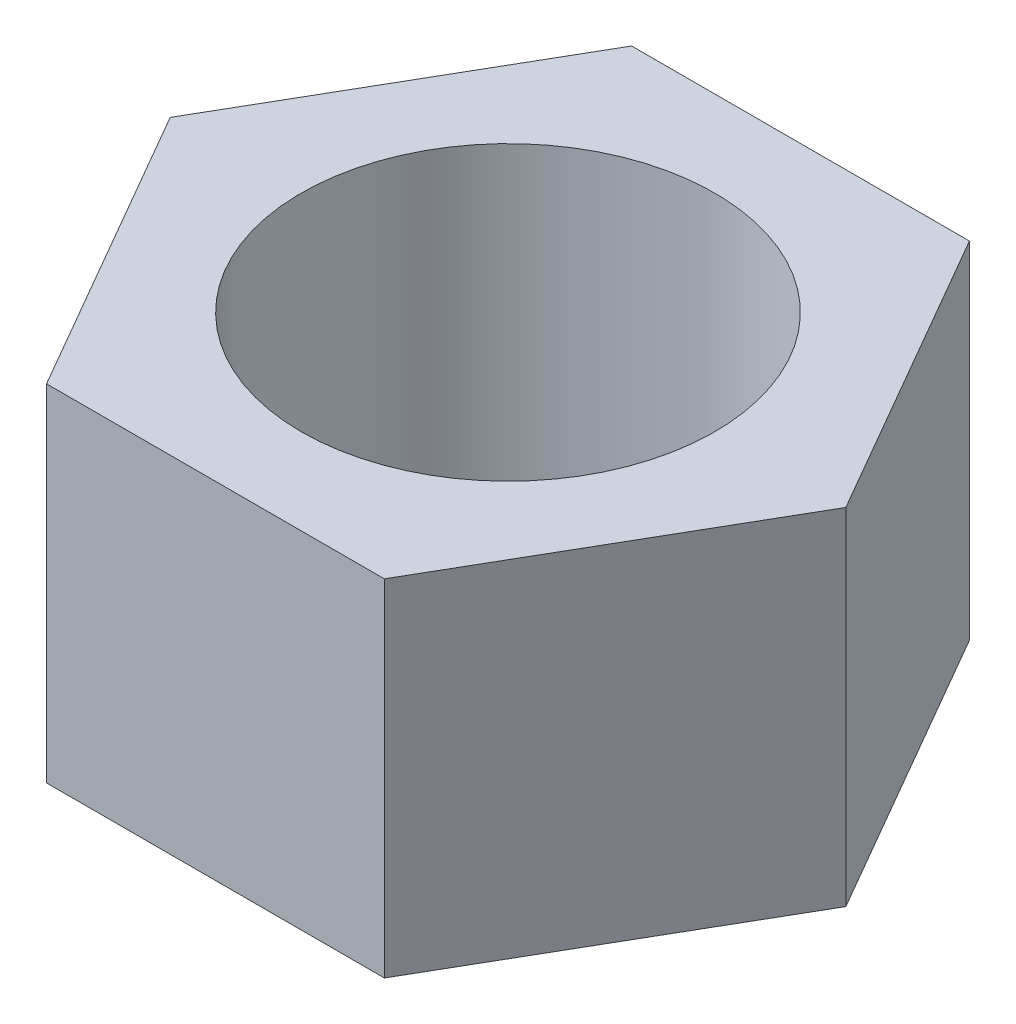
SolidWorks part; units mm, degrees
ref_plane "Front Plane" through (0, 0, 0) normal (0, 0, 1) x (1, 0, 0)
ref_plane "Top Plane" through (0, 0, 0) normal (0, 1, 0) x (1, 0, 0)
ref_plane "Right Plane" through (0, 0, 0) normal (1, 0, 0) x (0, 0, -1)
sketch "Sketch1" plane through (0, 0, 0) normal (0, 1, 0) x (1, 0, 0)
  line L1 (8.1695, 0) -> (4.0848, 7.075)
  line L2 (4.0848, 7.075) -> (-4.0848, 7.075)
  line L3 (-4.0848, 7.075) -> (-8.1695, 0)
  line L4 (-8.1695, 0) -> (-4.0848, -7.075)
  line L5 (-4.0848, -7.075) -> (4.0848, -7.075)
  line L6 (4.0848, -7.075) -> (8.1695, 0)
  circle A0 centre (0, 0) radius 7.075 construction
  dimension "D1" = 14.15
extrude "Boss-Extrude1" add sketch "Sketch1" along normal blind 8.36
sketch "Sketch2" plane through (0, 8.36, 0) normal (0, 1, 0) x (1, 0, 0)
  circle A0 centre (0, 0) radius 5
extrude "Cut-Extrude1" cut sketch "Sketch2" against normal blind 8.36
